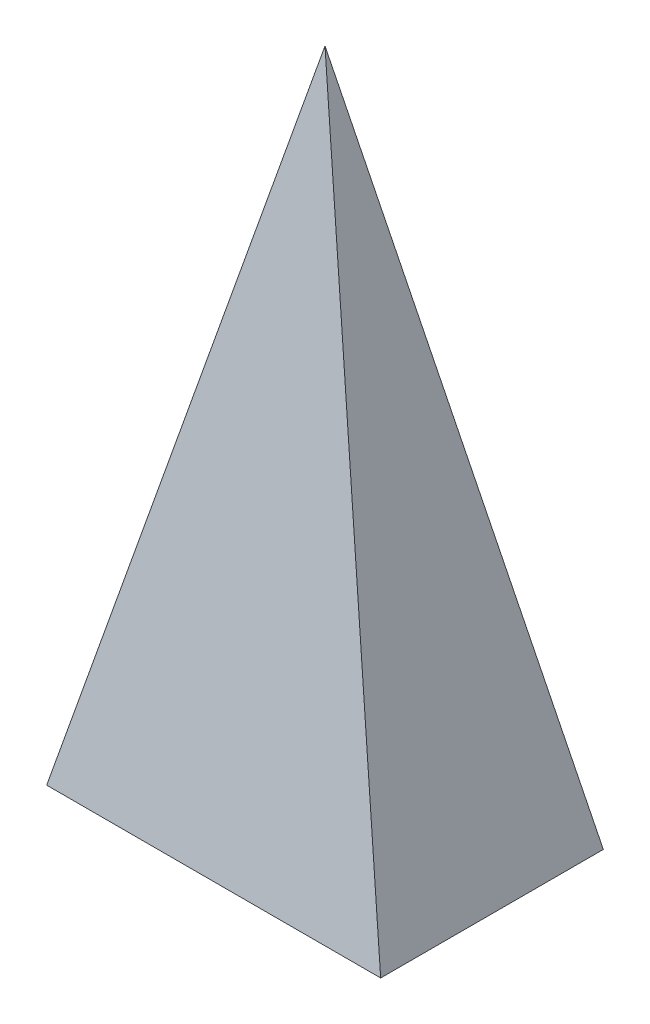
SolidWorks part; units mm, degrees
ref_plane "前视基准面" through (0, 0, 0) normal (0, 0, 1) x (1, 0, 0)
ref_plane "上视基准面" through (0, 0, 0) normal (0, 1, 0) x (1, 0, 0)
ref_plane "右视基准面" through (0, 0, 0) normal (1, 0, 0) x (0, 0, -1)
sketch "草图1" plane through (0, 0, 0) normal (0, 1, 0) x (1, 0, 0)
  line L1 (750, -500) -> (-750, -500)
  line L2 (750, -500) -> (750, 500)
  line L3 (750, 500) -> (-750, 500)
  line L4 (-750, -500) -> (-750, 500)
  line L5 (750, -500) -> (-750, 500) construction
  line L6 (750, 500) -> (-750, -500) construction
  point P0 (0, 0)
  dimension "D1" = 1500
  dimension "D2" = 1000
ref_plane "基准面4" through (0, 3000, 0) normal (0, 1, 0) x (1, 0, 0)
sketch "草图2" plane through (0, 3000, 0) normal (0, 1, 0) x (1, 0, 0)
  point P0 (0, 0)
loft "放样1" add profiles "草图1", "草图2"
